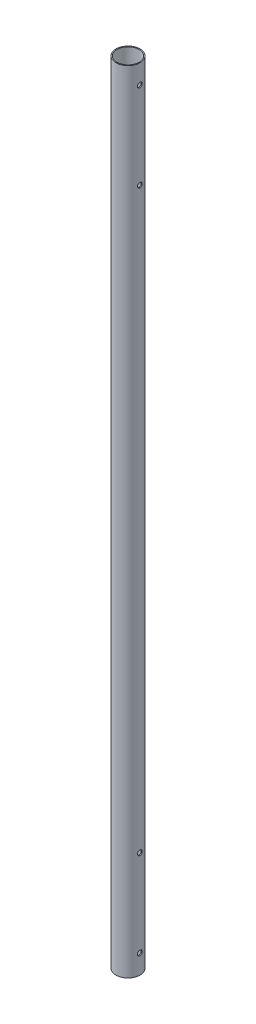
SolidWorks part; units mm, degrees
material "AISI 316 Отожженная нержавеющая сталь. полоса (SS)"
ref_plane "Спереди XY" through (0, 0, 0) normal (0, 0, 1) x (1, 0, 0)
ref_plane "Сверху XZ" through (0, 0, 0) normal (0, 1, 0) x (1, 0, 0)
ref_plane "Справа ZY" through (0, 0, 0) normal (1, 0, 0) x (0, 0, -1)
sketch "Эскиз1" plane through (0, 0, 0) normal (0, 1, 0) x (1, 0, 0)
  circle A0 centre (0, 0) radius 12.5
  dimension "D1" = 25
extrude "Вытянуть-Тонкостенный1" add sketch "Эскиз1" along normal blind 820 thin thin type one direction reverse wall 1
sketch "Эскиз2" plane through (0, 0, 0) normal (1, 0, 0) x (0, 0, -1)
  line L0 (0, 92.0221) -> (0, 50) construction
  line L1 (-12.5, 0) -> (12.5, 0) construction
  line L5 (0, 0) -> (0, -76.8772) construction
  circle A0 centre (0, 110) radius 2.5
  circle A2 centre (0, 20) radius 2.5
  dimension "D2" = 20
  dimension "D1" = 5
  dimension "D3" = 5
  dimension "D4" = 90
extrude "Вырез-Вытянуть1" cut sketch "Эскиз2" against normal through all both and the other way through all
ref_plane "Плоскость1" through (0, 410, 0) normal (0, -1, 0) x (-1, 0, 0)
mirror "Зеркальное отражение1" about plane through (0, 410, 0) normal (0, -1, 0) of "Вырез-Вытянуть1"
